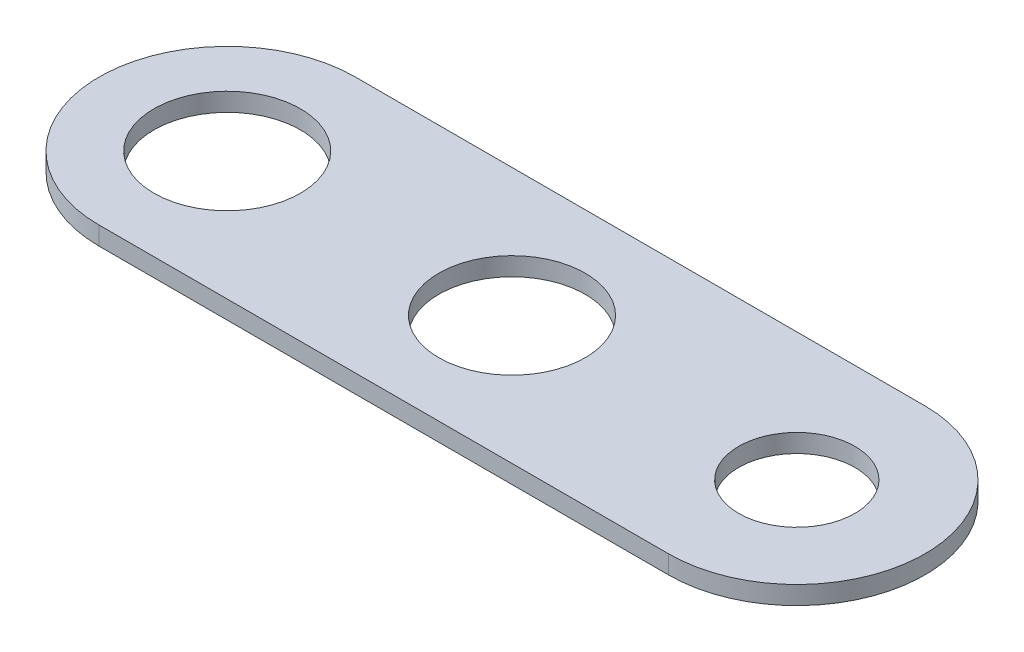
SolidWorks part; units mm, degrees
material "Delrin 2700 NC010, Low Viscosity Acetal Copolymer (SS)"
ref_plane "Front Plane" through (0, 0, 0) normal (0, 0, 1) x (1, 0, 0)
ref_plane "Top Plane" through (0, 0, 0) normal (0, 1, 0) x (1, 0, 0)
ref_plane "Right Plane" through (0, 0, 0) normal (1, 0, 0) x (0, 0, -1)
sketch "Sketch1" plane through (0, 0, 0) normal (0, 1, 0) x (1, 0, 0)
  line L0 (-15.555, 0) -> (15.555, 0) construction
  line L1 (-15.555, 7) -> (15.555, 7)
  line L2 (-15.555, -7) -> (15.555, -7)
  arc A0 (-15.555, 7) -> (-15.555, -7) centre (-15.555, 0) ccw
  arc A1 (15.555, -7) -> (15.555, 7) centre (15.555, 0) ccw
  circle A2 centre (-15.555, 0) radius 4
  circle A3 centre (0, 0) radius 4
  circle A4 centre (15.555, 0) radius 3.175
  point P2 (0, 0)
  dimension "D1" = 8
  dimension "D2" = 6.35
  dimension "D4" = 7
  dimension "D3" = 15.555
extrude "Boss-Extrude1" add sketch "Sketch1" along normal blind 1
